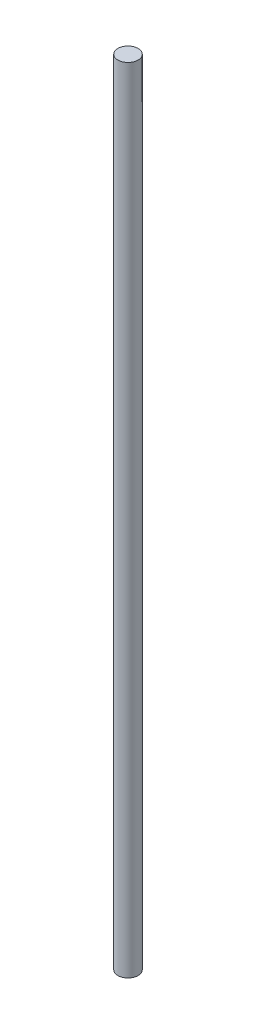
SolidWorks part; units mm, degrees
ref_plane "前视基准面" through (0, 0, 0) normal (0, 0, 1) x (1, 0, 0)
ref_plane "上视基准面" through (0, 0, 0) normal (0, 1, 0) x (1, 0, 0)
ref_plane "右视基准面" through (0, 0, 0) normal (1, 0, 0) x (0, 0, -1)
other "Configuration Table"
sketch "草图1" plane through (0, 0, 0) normal (0, 1, 0) x (1, 0, 0)
  circle A0 centre (0, 0) radius 2.8
  dimension "D1" = 5.6
extrude "凸台-拉伸1" add sketch "草图1" along normal blind 220
